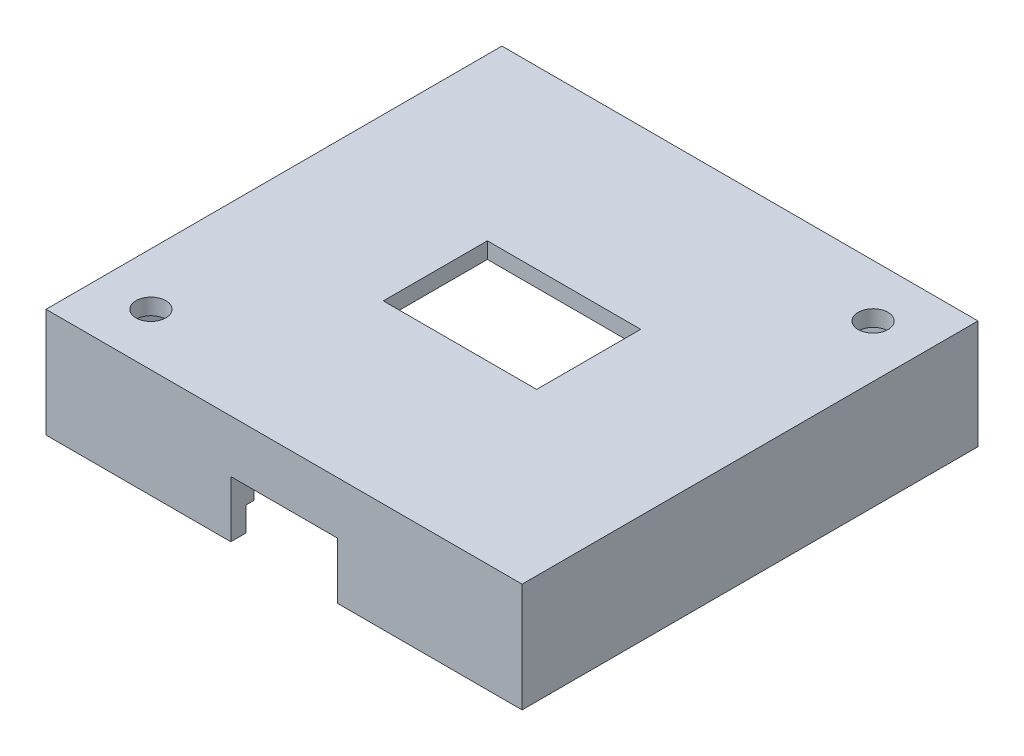
SolidWorks part; units mm, degrees
ref_plane "Front Plane" through (0, 0, 0) normal (0, 0, 1) x (1, 0, 0)
ref_plane "Top Plane" through (0, 0, 0) normal (0, 1, 0) x (1, 0, 0)
ref_plane "Right Plane" through (0, 0, 0) normal (1, 0, 0) x (0, 0, -1)
sketch "Sketch1" plane through (0, 0, 0) normal (0, 1, 0) x (1, 0, 0)
  line L1 (-29.5, -28.25) -> (29.5, -28.25)
  line L2 (-29.5, -28.25) -> (-29.5, 28.25)
  line L3 (-29.5, 28.25) -> (29.5, 28.25)
  line L4 (29.5, -28.25) -> (29.5, 28.25)
  line L5 (-29.5, -28.25) -> (29.5, 28.25) construction
  line L6 (-29.5, 28.25) -> (29.5, -28.25) construction
  point P0 (0, 0)
  dimension "D1" = 59
  dimension "D2" = 56.5
extrude "Boss-Extrude1" add sketch "Sketch1" along normal blind 13.5
sketch "Sketch2" plane through (0, 0, 0) normal (0, -1, 0) x (1, 0, 0)
  line L0 (29.5, -28.25) -> (-29.5, -28.25) construction
  line L1 (-27.6, -26.35) -> (27.6, -26.35)
  line L2 (-27.6, -26.35) -> (-27.6, 26.35)
  line L3 (-27.6, 26.35) -> (27.6, 26.35)
  line L4 (27.6, -26.35) -> (27.6, 26.35)
  line L5 (-27.6, -26.35) -> (27.6, 26.35) construction
  line L6 (-27.6, 26.35) -> (27.6, -26.35) construction
  line L9 (-29.5, -28.25) -> (-29.5, 28.25) construction
  point P0 (0, 0)
  dimension "D1" = 1.9
  dimension "D2" = 1.9
extrude "Cut-Extrude1" cut sketch "Sketch2" against normal offset from surface (11.5 mm away) 2 up to face at (0, 13.5, 0)
sketch "Sketch10" plane through (0, 13.5, 0) normal (0, 1, 0) x (1, 0, 0)
  line L1 (-9.5, -6.45) -> (9.5, -6.45)
  line L2 (-9.5, -6.45) -> (-9.5, 6.45)
  line L3 (-9.5, 6.45) -> (9.5, 6.45)
  line L4 (9.5, -6.45) -> (9.5, 6.45)
  line L5 (-9.5, -6.45) -> (9.5, 6.45) construction
  line L6 (-9.5, 6.45) -> (9.5, -6.45) construction
  line L7 (-29.5, 28.25) -> (-29.5, -28.25) construction
  point P0 (-9.5, 0)
  dimension "D1" = 19
  dimension "D2" = 12.9
  dimension "D3" = 20
extrude "Cut-Extrude4" cut sketch "Sketch10" against normal blind 10
sketch "Sketch15" plane through (0, 13.5, 0) normal (0, 1, 0) x (1, 0, 0)
  line L0 (0, 6.45) -> (0, -6.45) construction
  line L1 (9.5, 6.45) -> (-9.5, 6.45) construction
  line L2 (-9.5, -6.45) -> (9.5, -6.45) construction
sketch "Sketch11" plane through (-29.5, 0, 0) normal (-1, 0, 0) x (0, 0, 1)
  line L1 (-3.05, 0) -> (3.05, 0)
  line L2 (-3.05, 0) -> (-3.05, 2.5)
  line L3 (-3.05, 2.5) -> (3.05, 2.5)
  line L4 (3.05, 0) -> (3.05, 2.5)
  line L6 (-28.25, 0) -> (28.25, 0) construction
  point P7 (0, 2.5)
  dimension "D2" = 2.5
  dimension "D3" = 6.1
extrude "Cut-Extrude5" cut sketch "Sketch11" against normal blind 10
sketch "Sketch12" plane through (0, 0, -28.25) normal (0, 0, -1) x (-1, 0, 0)
  line L0 (-29.5, 13.5) -> (29.5, 13.5) construction
  line L1 (-6.25, 0) -> (6.25, 0)
  line L2 (-6.25, 0) -> (-6.25, 11.5)
  line L3 (-6.25, 11.5) -> (6.25, 11.5)
  line L4 (6.25, 0) -> (6.25, 11.5)
  point P7 (0, 11.5)
  dimension "D1" = 12.5
  dimension "D2" = 11.5
  dimension "D3" = 2
extrude "Cut-Extrude6" cut sketch "Sketch12" against normal blind 10
sketch "Sketch13" plane through (0, 0, 28.25) normal (0, 0, 1) x (1, 0, 0)
  line L1 (-6.6, 7) -> (6.6, 7)
  line L2 (-6.6, 7) -> (-6.6, 0)
  line L3 (-6.6, 0) -> (6.6, 0)
  line L4 (6.6, 7) -> (6.6, 0)
  line L7 (-29.5, 13.5) -> (29.5, 13.5) construction
  line L8 (-29.5, 0) -> (29.5, 0) construction
  point P8 (0, 7)
  dimension "D1" = 6.5
  dimension "D2" = 13.2
extrude "Cut-Extrude7" cut sketch "Sketch13" against normal blind 10
sketch "Sketch14" plane through (0, 11.5, 0) normal (0, -1, 0) x (1, 0, 0)
  line L0 (-26.6, 25.35) -> (-26.6, 3.05)
  line L1 (-27.6, 26.35) -> (-6.6, 26.35)
  line L2 (-27.6, 26.35) -> (-27.6, 3.05)
  line L3 (-27.6, -26.35) -> (-6.25, -26.35)
  line L4 (27.6, 26.35) -> (27.6, -26.35)
  line L5 (-26.6, -25.35) -> (-6.25, -25.35)
  line L6 (26.6, 25.35) -> (26.6, -25.35)
  line L7 (-26.6, 25.35) -> (-6.6, 25.35)
  line L8 (-6.6, 25.35) -> (-6.6, 26.35)
  line L9 (6.6, 25.35) -> (6.6, 26.35)
  line L10 (-26.6, -3.05) -> (-27.6, -3.05)
  line L11 (-26.6, 3.05) -> (-27.6, 3.05)
  line L12 (-6.25, -25.35) -> (-6.25, -26.35)
  line L13 (6.25, -25.35) -> (6.25, -26.35)
  line L14 (-6.6, 26.35) -> (-6.6, 28.25) construction
  line L15 (6.6, 26.35) -> (6.6, 28.25) construction
  line L16 (-27.6, -3.05) -> (-29.5, -3.05) construction
  line L17 (-27.6, 3.05) -> (-29.5, 3.05) construction
  line L18 (-6.25, -26.35) -> (-6.25, -28.25) construction
  line L19 (6.25, -26.35) -> (6.25, -28.25) construction
  line L20 (6.25, -26.35) -> (27.6, -26.35)
  line L21 (-27.6, -26.35) -> (27.6, -26.35) construction
  line L22 (6.25, -25.35) -> (26.6, -25.35)
  line L23 (-26.6, -25.35) -> (26.6, -25.35) construction
  line L24 (-26.6, -3.05) -> (-26.6, -25.35)
  line L25 (-26.6, 25.35) -> (-26.6, -25.35) construction
  line L26 (-27.6, -3.05) -> (-27.6, -26.35)
  line L27 (-27.6, 26.35) -> (-27.6, -26.35) construction
  line L28 (6.6, 25.35) -> (26.6, 25.35)
  line L29 (-26.6, 25.35) -> (26.6, 25.35) construction
  line L30 (6.6, 26.35) -> (27.6, 26.35)
  line L31 (-27.6, 26.35) -> (27.6, 26.35) construction
  dimension "D2" = 0
  dimension "D3" = 0
  dimension "D4" = 0
  dimension "D5" = 0
  dimension "D6" = 0
  dimension "D7" = 0
  dimension "D1" = 1
extrude "Boss-Extrude2" add sketch "Sketch14" along normal offset from surface (8.5 mm away) 3 up to face at (-21.1167, 0, -19.2167)
sketch "Sketch16" plane through (0, 13.5, 0) normal (0, 1, 0) x (1, 0, 0)
  line L0 (29.5, 28.25) -> (-29.5, 28.25) construction
  line L1 (-29.5, 28.25) -> (-29.5, -28.25) construction
  line L2 (0, 28.25) -> (0, -28.25) construction
  line L3 (-29.5, -28.25) -> (29.5, -28.25) construction
  line L4 (-29.5, 0) -> (29.5, 0) construction
  line L5 (29.5, -28.25) -> (29.5, 28.25) construction
  circle A1 centre (23, 21.75) radius 1.8526
  circle A3 centre (-23, -21.75) radius 1.8526
  dimension "D1" = 3.7052
  dimension "D2" = 3.7052
  dimension "D3" = 6.5
  dimension "D4" = 6.5
  dimension "D5" = 6.5
  dimension "D6" = 6.5
extrude "Cut-Extrude8" cut sketch "Sketch16" against normal blind 3
